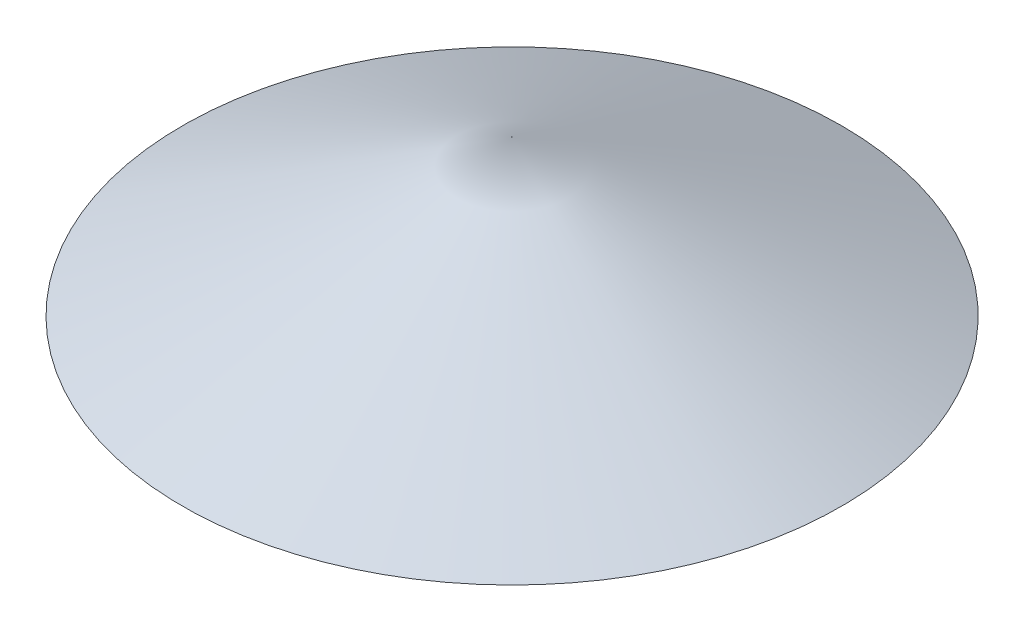
SolidWorks part; units mm, degrees
material "Prata-níquel 65-12, UNS C75700"
ref_plane "Plano frontal" through (0, 0, 0) normal (0, 0, 1) x (1, 0, 0)
ref_plane "Plano superior" through (0, 0, 0) normal (0, 1, 0) x (1, 0, 0)
ref_plane "Plano direito" through (0, 0, 0) normal (1, 0, 0) x (0, 0, -1)
sketch "Esboço1" plane through (0, 0, 0) normal (0, 0, 1) x (1, 0, 0)
  line L0 (0, 0) -> (0, 0.4)
  line L1 (0, 0) -> (-0.85, 0)
  line L2 (-0.85, 0) -> (0, 0.4)
  dimension "D1" = 0.4
  dimension "D2" = 0.85
revolve "Revolução1" add sketch "Esboço1" angle 360 about L0
